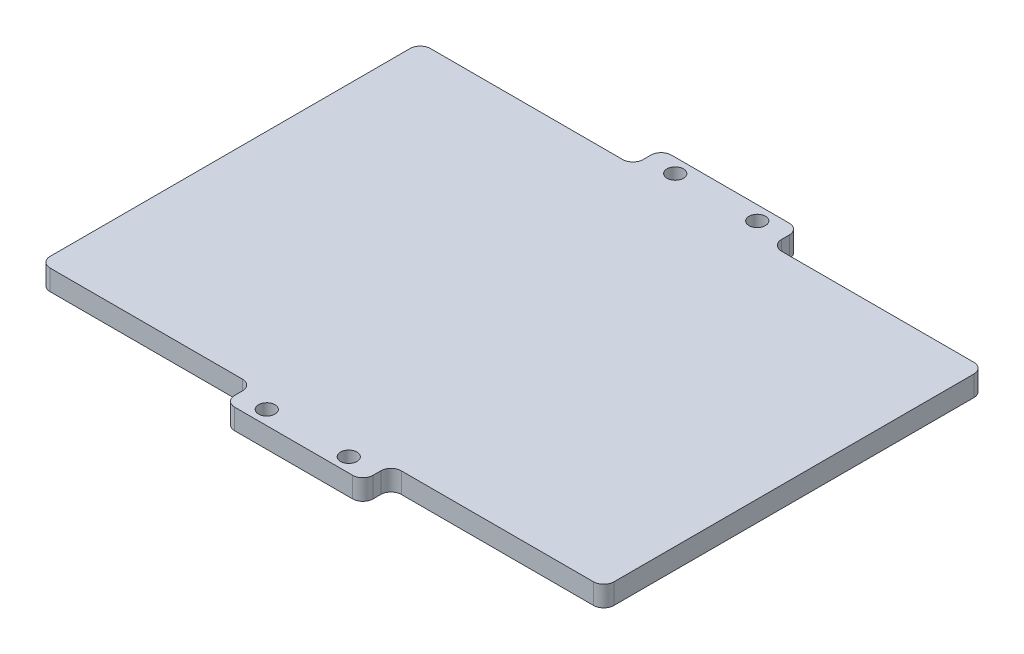
SolidWorks part; units mm, degrees
ref_plane "前视基准面" through (0, 0, 0) normal (0, 0, 1) x (1, 0, 0)
ref_plane "上视基准面" through (0, 0, 0) normal (0, 1, 0) x (1, 0, 0)
ref_plane "右视基准面" through (0, 0, 0) normal (1, 0, 0) x (0, 0, -1)
sketch "草图1" plane through (0, 0, 0) normal (0, 1, 0) x (1, 0, 0)
  line L1 (-55, -42.6) -> (55, -42.6)
  line L2 (-55, -42.6) -> (-55, 42.6)
  line L3 (-55, 42.6) -> (55, 42.6)
  line L4 (55, -42.6) -> (55, 42.6)
  line L5 (-55, -42.6) -> (55, 42.6) construction
  line L6 (-55, 42.6) -> (55, -42.6) construction
  point P0 (0, 0)
  dimension "D1" = 85.2
  dimension "D2" = 110
extrude "凸台-拉伸1" add sketch "草图1" along normal blind 4
sketch "草图2" plane through (0, 4, 0) normal (0, 1, 0) x (1, 0, 0)
  line L0 (-55, 0) -> (55, 0) construction
  line L1 (-55, 42.6) -> (-55, -42.6) construction
  line L2 (55, -42.6) -> (55, 42.6) construction
  line L3 (0, 42.6) -> (0, -42.6) construction
  line L4 (55, 42.6) -> (-55, 42.6) construction
  line L5 (-55, -42.6) -> (55, -42.6) construction
  line L6 (96.5, -48.1) -> (13.5, -37.1) construction
  line L7 (-96.5, -37.1) -> (-13.5, -37.1)
  line L8 (-96.5, -37.1) -> (-96.5, -48.1)
  line L9 (-96.5, -48.1) -> (-13.5, -48.1)
  line L10 (-13.5, -37.1) -> (-13.5, -48.1)
  line L11 (-96.5, -37.1) -> (-13.5, -48.1) construction
  line L12 (-96.5, -48.1) -> (-13.5, -37.1) construction
  line L13 (96.5, -37.1) -> (13.5, -48.1) construction
  line L14 (13.5, -37.1) -> (13.5, -48.1)
  line L15 (96.5, -48.1) -> (13.5, -48.1)
  line L16 (96.5, -37.1) -> (96.5, -48.1)
  line L17 (96.5, -37.1) -> (13.5, -37.1)
  line L18 (96.5, 37.1) -> (13.5, 48.1) construction
  line L19 (96.5, 37.1) -> (13.5, 37.1)
  line L20 (96.5, 37.1) -> (96.5, 48.1)
  line L21 (96.5, 48.1) -> (13.5, 37.1) construction
  line L22 (96.5, 48.1) -> (13.5, 48.1)
  line L23 (13.5, 37.1) -> (13.5, 48.1)
  line L24 (-96.5, 48.1) -> (-13.5, 37.1) construction
  line L25 (-96.5, 37.1) -> (-13.5, 48.1) construction
  line L26 (-13.5, 37.1) -> (-13.5, 48.1)
  line L27 (-96.5, 48.1) -> (-13.5, 48.1)
  line L28 (-96.5, 37.1) -> (-96.5, 48.1)
  line L29 (-96.5, 37.1) -> (-13.5, 37.1)
  point P12 (-55, -42.6)
  point P22 (55, -42.6)
  point P27 (55, 42.6)
  point P32 (-55, 42.6)
  dimension "D1" = 13.5
  dimension "D2" = 11
extrude "切除-拉伸1" cut sketch "草图2" against normal blind 4
sketch "草图3" plane through (0, 4, 0) normal (0, 1, 0) x (1, 0, 0)
  line L0 (0, 42.6) -> (0, -42.6) construction
  line L1 (13.5, 42.6) -> (-13.5, 42.6) construction
  line L2 (-13.5, -42.6) -> (13.5, -42.6) construction
  line L3 (-55, 0) -> (55, 0) construction
  line L4 (-55, 37.1) -> (-55, -37.1) construction
  line L5 (55, -37.1) -> (55, 37.1) construction
  circle A0 centre (-8, -39.85) radius 1.6
  circle A1 centre (8, -39.85) radius 1.6
  circle A2 centre (8, 39.85) radius 1.6
  circle A3 centre (-8, 39.85) radius 1.6
  dimension "D1" = 3.2
  dimension "D2" = 2.75
  dimension "D3" = 16
extrude "切除-拉伸2" cut sketch "草图3" against normal blind 4
fillet "圆角1" radius 2 12 edges at (-13.5, 2, 42.6) (-13.5, 2, 37.1) (-55, 2, 37.1) (-13.5, 2, -37.1) (-13.5, 2, -42.6) (13.5, 2, -42.6) (13.5, 2, -37.1) (55, 2, -37.1) (55, 2, 37.1) (13.5, 2, 37.1) (13.5, 2, 42.6) (-55, 2, -37.1)
